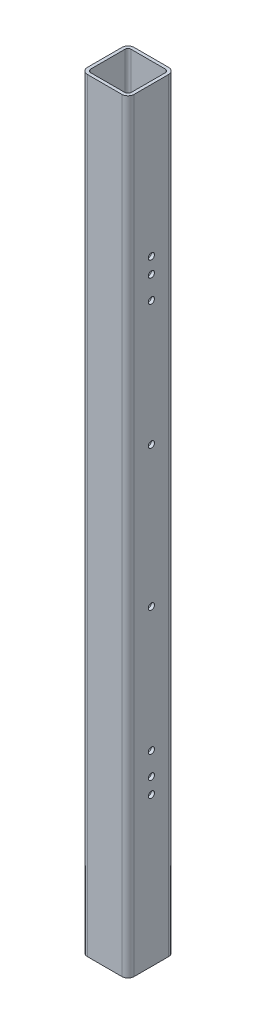
SolidWorks part; units mm, degrees
material "AISI 1010 钢，热轧条材"
ref_plane "前视基准面" through (0, 0, 0) normal (0, 0, 1) x (1, 0, 0)
ref_plane "上视基准面" through (0, 0, 0) normal (0, 1, 0) x (1, 0, 0)
ref_plane "右视基准面" through (0, 0, 0) normal (1, 0, 0) x (0, 0, -1)
sketch "草图1" plane through (0, 0, 0) normal (0, 1, 0) x (1, 0, 0)
  line L0 (4, 2) -> (26, 2)
  line L1 (4, 0) -> (26, 0)
  line L2 (0, 4) -> (0, 26)
  line L3 (4, 30) -> (26, 30)
  line L4 (30, 4) -> (30, 26)
  line L5 (28, 4) -> (28, 26)
  line L6 (4, 28) -> (26, 28)
  line L7 (2, 4) -> (2, 26)
  arc A0 (4, 0) -> (0, 4) centre (4, 4) cw
  arc A1 (26, 0) -> (30, 4) centre (26, 4) ccw
  arc A2 (26, 30) -> (30, 26) centre (26, 26) cw
  arc A3 (0, 26) -> (4, 30) centre (4, 26) cw
  arc A4 (26, 2) -> (28, 4) centre (26, 4) ccw
  arc A5 (26, 28) -> (28, 26) centre (26, 26) cw
  arc A6 (2, 26) -> (4, 28) centre (4, 26) cw
  arc A7 (4, 2) -> (2, 4) centre (4, 4) cw
  point P7 (0, 0)
  point P10 (30, 0)
  point P13 (30, 30)
  point P16 (0, 30)
  dimension "D3" = 4
  dimension "D1" = 30
  dimension "D2" = 30
  dimension "D4" = 2
extrude "凸台-拉伸1" add sketch "草图1" along normal mid plane 490
sketch "草图2" plane through (0, 0, 0) normal (0, 0, 1) x (1, 0, 0)
  line L0 (0, 245) -> (0, -245) construction
  circle A0 centre (15, 140) radius 2.5
  circle A1 centre (15, 90) radius 2.5
  circle A2 centre (15, 63) radius 2.5
  circle A3 centre (15, 43) radius 2.5
  dimension "D1" = 5
  dimension "D2" = 15
  dimension "D3" = 90
  dimension "D4" = 50
  dimension "D5" = 20
  dimension "D6" = 43
sketch "草图3" plane through (0, 0, 0) normal (1, 0, 0) x (0, 0, -1)
  line L0 (15, 144.5) -> (15, -144.5) construction
  line L1 (4, 245) -> (26, 245) construction
  line L2 (0, 0) -> (30, 0) construction
  line L3 (30, 245) -> (30, -245) construction
  line L5 (4, -245) -> (26, -245) construction
  circle A0 centre (15, -149.5) radius 2
  circle A1 centre (15, -139.5) radius 2
  circle A2 centre (15, 139.5) radius 2
  circle A3 centre (15, 149.5) radius 2
  circle A6 centre (15, 125) radius 2
  circle A7 centre (15, 45) radius 2
  circle A8 centre (15, -45) radius 2
  circle A9 centre (15, -125) radius 2
  point P2 (15, 0)
  point P7 (15, 245)
  dimension "D2" = 4
  dimension "D5" = 4
  dimension "D1" = 95.5
  dimension "D3" = 10
  dimension "D4" = 5
  dimension "D6" = 120
  dimension "D7" = 80
extrude "切除-拉伸2" cut sketch "草图3" along normal through all and the other way through all
